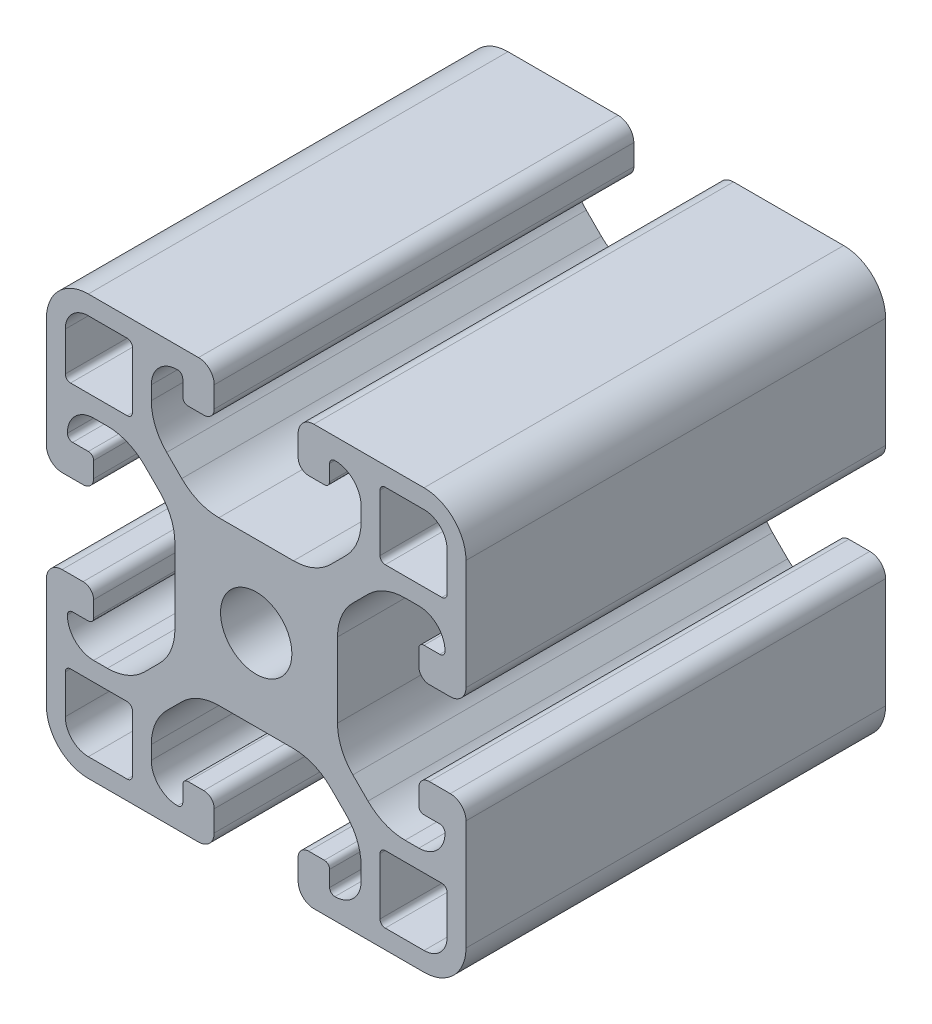
SolidWorks part; units mm, degrees
ref_plane "Plan de face" through (0, 0, 0) normal (0, 0, 1) x (1, 0, 0)
ref_plane "Plan de dessus" through (0, 0, 0) normal (0, 1, 0) x (1, 0, 0)
ref_plane "Plan de droite" through (0, 0, 0) normal (1, 0, 0) x (0, 0, -1)
ref_plane "Plan1" through (0, 0, -30) normal (0, 0, -1) x (-1, 0, 0)
sketch "Esquisse1" plane through (0, 0, -30) normal (0, 0, -1) x (-1, 0, 0)
  line B0 (-4.5, 15) -> (-4.5, 13.5)
  line B1 (-4, 13) -> (-2.5, 13)
  line B2 (-4.5, 10) -> (-5.8076, 10)
  line B3 (-9.3431, 11.4645) -> (-10.7855, 12.9069)
  line B4 (-12.25, 16.4424) -> (-12.25, 23.5576)
  line B5 (-10.7855, 27.0931) -> (-9.3431, 28.5355)
  line B6 (-5.8076, 30) -> (-4.5, 30)
  line B7 (-2.5, 27) -> (-4, 27)
  line B8 (-4.5, 26.5) -> (-4.5, 25)
  line B9 (-3.5, 24) -> (-1.5, 24)
  line B10 (0, 25.5) -> (0, 36)
  line B11 (-4, 40) -> (-14.5, 40)
  line B12 (-16, 38.5) -> (-16, 36.5)
  line B13 (-15, 35.5) -> (-13.5, 35.5)
  line B14 (-13, 36) -> (-13, 37.5)
  line B15 (-10, 35.5) -> (-10, 34.1924)
  line B16 (-11.4645, 30.6569) -> (-12.9069, 29.2145)
  line B17 (-16.4424, 27.75) -> (-23.5576, 27.75)
  line B18 (-27.0931, 29.2145) -> (-28.5355, 30.6569)
  line B19 (-30, 34.1924) -> (-30, 35.5)
  line B20 (-27, 37.5) -> (-27, 36)
  line B21 (-26.5, 35.5) -> (-25, 35.5)
  line B22 (-24, 36.5) -> (-24, 38.5)
  line B23 (-25.5, 40) -> (-36, 40)
  line B24 (-40, 36) -> (-40, 25.5)
  line B25 (-38.5, 24) -> (-36.5, 24)
  line B26 (-35.5, 25) -> (-35.5, 26.5)
  line B27 (-36, 27) -> (-37.5, 27)
  line B28 (-35.5, 30) -> (-34.1924, 30)
  line B29 (-30.6569, 28.5355) -> (-29.2145, 27.0931)
  line B30 (-27.75, 23.5576) -> (-27.75, 16.4424)
  line B31 (-29.2145, 12.9069) -> (-30.6569, 11.4645)
  line B32 (-34.1924, 10) -> (-35.5, 10)
  line B33 (-37.5, 13) -> (-36, 13)
  line B34 (-35.5, 13.5) -> (-35.5, 15)
  line B35 (-36.5, 16) -> (-38.5, 16)
  line B36 (-40, 14.5) -> (-40, 4)
  line B37 (-36, 0) -> (-25.5, 0)
  line B38 (-24, 1.5) -> (-24, 3.5)
  line B39 (-25, 4.5) -> (-26.5, 4.5)
  line B40 (-27, 4) -> (-27, 2.5)
  line B41 (-30, 4.5) -> (-30, 5.8076)
  line B42 (-28.5355, 9.3431) -> (-27.0931, 10.7855)
  line B43 (-23.5576, 12.25) -> (-16.4424, 12.25)
  line B44 (-12.9069, 10.7855) -> (-11.4645, 9.3431)
  line B45 (-10, 5.8076) -> (-10, 4.5)
  line B46 (-13, 2.5) -> (-13, 4)
  line B47 (-13.5, 4.5) -> (-15, 4.5)
  line B48 (-16, 3.5) -> (-16, 1.5)
  line B49 (-14.5, 0) -> (-4, 0)
  line B50 (0, 4) -> (0, 14.5)
  line B51 (-1.5, 16) -> (-3.5, 16)
  line B52 (-4, 1.8) -> (-7.7, 1.8)
  line B53 (-8.2, 2.3) -> (-8.2, 7.7)
  line B54 (-7.7, 8.2) -> (-2.3, 8.2)
  line B55 (-1.8, 7.7) -> (-1.8, 4)
  line B56 (-38.2, 4) -> (-38.2, 7.7)
  line B57 (-37.7, 8.2) -> (-32.3, 8.2)
  line B58 (-31.8, 7.7) -> (-31.8, 2.3)
  line B59 (-32.3, 1.8) -> (-36, 1.8)
  line B60 (-36, 38.2) -> (-32.3, 38.2)
  line B61 (-31.8, 37.7) -> (-31.8, 32.3)
  line B62 (-32.3, 31.8) -> (-37.7, 31.8)
  line B63 (-38.2, 32.3) -> (-38.2, 36)
  line B64 (-1.8, 36) -> (-1.8, 32.3)
  line B65 (-2.3, 31.8) -> (-7.7, 31.8)
  line B66 (-8.2, 32.3) -> (-8.2, 37.7)
  line B67 (-7.7, 38.2) -> (-4, 38.2)
  arc B68 (-4.5, 13.5) -> (-4, 13) centre (-4, 13.5) ccw
  arc B69 (-2.5, 13) -> (-2, 12.5) centre (-2.5, 12.5) cw
  arc B70 (-2, 12.5) -> (-4.5, 10) centre (-4.5, 12.5) cw
  arc B71 (-5.8076, 10) -> (-9.3431, 11.4645) centre (-5.8076, 15) cw
  arc B72 (-10.7855, 12.9069) -> (-12.25, 16.4424) centre (-7.25, 16.4424) cw
  arc B73 (-12.25, 23.5576) -> (-10.7855, 27.0931) centre (-7.25, 23.5576) cw
  arc B74 (-9.3431, 28.5355) -> (-5.8076, 30) centre (-5.8076, 25) cw
  arc B75 (-4.5, 30) -> (-2, 27.5) centre (-4.5, 27.5) cw
  arc B76 (-2, 27.5) -> (-2.5, 27) centre (-2.5, 27.5) cw
  arc B77 (-4, 27) -> (-4.5, 26.5) centre (-4, 26.5) ccw
  arc B78 (-4.5, 25) -> (-3.5, 24) centre (-3.5, 25) ccw
  arc B79 (-1.5, 24) -> (0, 25.5) centre (-1.5, 25.5) ccw
  arc B80 (0, 36) -> (-4, 40) centre (-4, 36) ccw
  arc B81 (-14.5, 40) -> (-16, 38.5) centre (-14.5, 38.5) ccw
  arc B82 (-16, 36.5) -> (-15, 35.5) centre (-15, 36.5) ccw
  arc B83 (-13.5, 35.5) -> (-13, 36) centre (-13.5, 36) ccw
  arc B84 (-13, 37.5) -> (-12.5, 38) centre (-12.5, 37.5) cw
  arc B85 (-12.5, 38) -> (-10, 35.5) centre (-12.5, 35.5) cw
  arc B86 (-10, 34.1924) -> (-11.4645, 30.6569) centre (-15, 34.1924) cw
  arc B87 (-12.9069, 29.2145) -> (-16.4424, 27.75) centre (-16.4424, 32.75) cw
  arc B88 (-23.5576, 27.75) -> (-27.0931, 29.2145) centre (-23.5576, 32.75) cw
  arc B89 (-28.5355, 30.6569) -> (-30, 34.1924) centre (-25, 34.1924) cw
  arc B90 (-30, 35.5) -> (-27.5, 38) centre (-27.5, 35.5) cw
  arc B91 (-27.5, 38) -> (-27, 37.5) centre (-27.5, 37.5) cw
  arc B92 (-27, 36) -> (-26.5, 35.5) centre (-26.5, 36) ccw
  arc B93 (-25, 35.5) -> (-24, 36.5) centre (-25, 36.5) ccw
  arc B94 (-24, 38.5) -> (-25.5, 40) centre (-25.5, 38.5) ccw
  arc B95 (-36, 40) -> (-40, 36) centre (-36, 36) ccw
  arc B96 (-40, 25.5) -> (-38.5, 24) centre (-38.5, 25.5) ccw
  arc B97 (-36.5, 24) -> (-35.5, 25) centre (-36.5, 25) ccw
  arc B98 (-35.5, 26.5) -> (-36, 27) centre (-36, 26.5) ccw
  arc B99 (-37.5, 27) -> (-38, 27.5) centre (-37.5, 27.5) cw
  arc B100 (-38, 27.5) -> (-35.5, 30) centre (-35.5, 27.5) cw
  arc B101 (-34.1924, 30) -> (-30.6569, 28.5355) centre (-34.1924, 25) cw
  arc B102 (-29.2145, 27.0931) -> (-27.75, 23.5576) centre (-32.75, 23.5576) cw
  arc B103 (-27.75, 16.4424) -> (-29.2145, 12.9069) centre (-32.75, 16.4424) cw
  arc B104 (-30.6569, 11.4645) -> (-34.1924, 10) centre (-34.1924, 15) cw
  arc B105 (-35.5, 10) -> (-38, 12.5) centre (-35.5, 12.5) cw
  arc B106 (-38, 12.5) -> (-37.5, 13) centre (-37.5, 12.5) cw
  arc B107 (-36, 13) -> (-35.5, 13.5) centre (-36, 13.5) ccw
  arc B108 (-35.5, 15) -> (-36.5, 16) centre (-36.5, 15) ccw
  arc B109 (-38.5, 16) -> (-40, 14.5) centre (-38.5, 14.5) ccw
  arc B110 (-40, 4) -> (-36, 0) centre (-36, 4) ccw
  arc B111 (-25.5, 0) -> (-24, 1.5) centre (-25.5, 1.5) ccw
  arc B112 (-24, 3.5) -> (-25, 4.5) centre (-25, 3.5) ccw
  arc B113 (-26.5, 4.5) -> (-27, 4) centre (-26.5, 4) ccw
  arc B114 (-27, 2.5) -> (-27.5, 2) centre (-27.5, 2.5) cw
  arc B115 (-27.5, 2) -> (-30, 4.5) centre (-27.5, 4.5) cw
  arc B116 (-30, 5.8076) -> (-28.5355, 9.3431) centre (-25, 5.8076) cw
  arc B117 (-27.0931, 10.7855) -> (-23.5576, 12.25) centre (-23.5576, 7.25) cw
  arc B118 (-16.4424, 12.25) -> (-12.9069, 10.7855) centre (-16.4424, 7.25) cw
  arc B119 (-11.4645, 9.3431) -> (-10, 5.8076) centre (-15, 5.8076) cw
  arc B120 (-10, 4.5) -> (-12.5, 2) centre (-12.5, 4.5) cw
  arc B121 (-12.5, 2) -> (-13, 2.5) centre (-12.5, 2.5) cw
  arc B122 (-13, 4) -> (-13.5, 4.5) centre (-13.5, 4) ccw
  arc B123 (-15, 4.5) -> (-16, 3.5) centre (-15, 3.5) ccw
  arc B124 (-16, 1.5) -> (-14.5, 0) centre (-14.5, 1.5) ccw
  arc B125 (-4, 0) -> (0, 4) centre (-4, 4) ccw
  arc B126 (0, 14.5) -> (-1.5, 16) centre (-1.5, 14.5) ccw
  arc B127 (-3.5, 16) -> (-4.5, 15) centre (-3.5, 15) ccw
  circle B128 centre (-20, 20) radius 3.4
  arc B129 (-1.8, 4) -> (-4, 1.8) centre (-4, 4) cw
  arc B130 (-7.7, 1.8) -> (-8.2, 2.3) centre (-7.7, 2.3) cw
  arc B131 (-8.2, 7.7) -> (-7.7, 8.2) centre (-7.7, 7.7) cw
  arc B132 (-2.3, 8.2) -> (-1.8, 7.7) centre (-2.3, 7.7) cw
  arc B133 (-36, 1.8) -> (-38.2, 4) centre (-36, 4) cw
  arc B134 (-38.2, 7.7) -> (-37.7, 8.2) centre (-37.7, 7.7) cw
  arc B135 (-32.3, 8.2) -> (-31.8, 7.7) centre (-32.3, 7.7) cw
  arc B136 (-31.8, 2.3) -> (-32.3, 1.8) centre (-32.3, 2.3) cw
  arc B137 (-38.2, 36) -> (-36, 38.2) centre (-36, 36) cw
  arc B138 (-32.3, 38.2) -> (-31.8, 37.7) centre (-32.3, 37.7) cw
  arc B139 (-31.8, 32.3) -> (-32.3, 31.8) centre (-32.3, 32.3) cw
  arc B140 (-37.7, 31.8) -> (-38.2, 32.3) centre (-37.7, 32.3) cw
  arc B141 (-4, 38.2) -> (-1.8, 36) centre (-4, 36) cw
  arc B142 (-1.8, 32.3) -> (-2.3, 31.8) centre (-2.3, 32.3) cw
  arc B143 (-7.7, 31.8) -> (-8.2, 32.3) centre (-7.7, 32.3) cw
  arc B144 (-8.2, 37.7) -> (-7.7, 38.2) centre (-7.7, 37.7) cw
sketch_block_instance "Bloc1-1"
sketch_block "Bloc1"
extrude "Boss.-Extru.1" add sketch "Esquisse1" against normal blind 40
